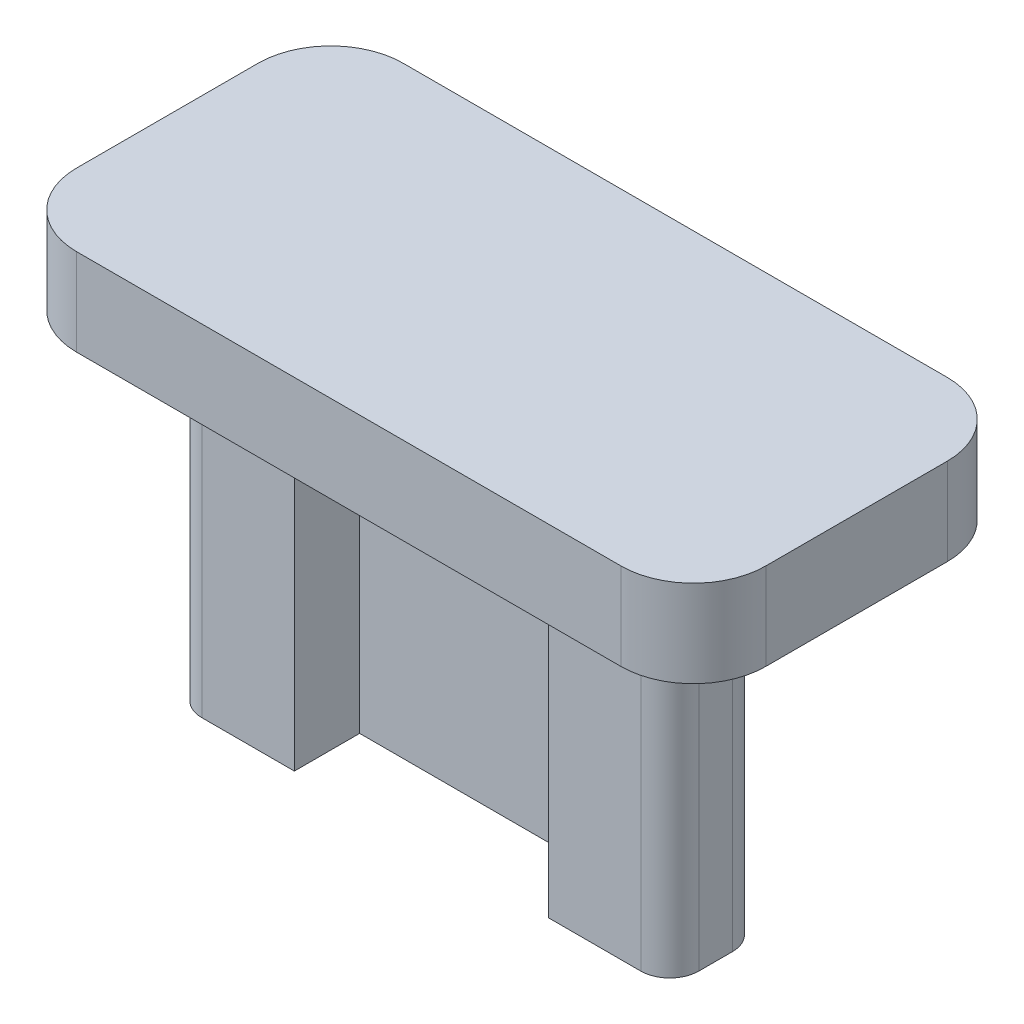
SolidWorks part; units mm, degrees
material "Rubber"
ref_plane "Front Plane" through (0, 0, 0) normal (0, 0, 1) x (1, 0, 0)
ref_plane "Top Plane" through (0, 0, 0) normal (0, 1, 0) x (1, 0, 0)
ref_plane "Right Plane" through (0, 0, 0) normal (1, 0, 0) x (0, 0, -1)
ref_plane "Plane1" through (0, 3.3, 0) normal (0, 1, 0) x (1, 0, 0)
sketch "Sketch1" plane through (0, 3.3, 0) normal (0, 1, 0) x (1, 0, 0)
  line L0 (4.75, -1.9) -> (4.75, 2.6)
  line L1 (4.75, 2.6) -> (-4.75, 2.6)
  line L2 (-4.75, 2.6) -> (-4.75, -1.9)
  line L3 (-4.75, -1.9) -> (4.75, -1.9)
  point P4 (0, 0)
  point P5 (0, -1.9)
extrude "Boss-Extrude1" add sketch "Sketch1" against normal blind 1.2
sketch "Sketch2" plane through (0, 2.1, 0) normal (0, -1, 0) x (1, 0, 0)
  line L0 (3.425, -0.13) -> (2.65, -0.9)
  line L1 (2.65, -0.9) -> (-2.65, -0.9)
  line L2 (-2.65, -0.9) -> (-3.425, -0.13)
  line L3 (-3.425, -0.13) -> (-3.425, 0.9)
  line L4 (-3.425, 0.9) -> (3.425, 0.9)
  line L5 (3.425, 0.9) -> (3.425, -0.13)
extrude "Boss-Extrude2" add sketch "Sketch2" along normal blind 4.5
sketch "Sketch4" plane through (0, -2.4, 0) normal (0, -1, 0) x (1, 0, 0)
  line L0 (1.75, 0.9) -> (-1.75, 0.9)
  line L1 (-1.75, 0.9) -> (-1.75, 0)
  line L2 (-1.75, 0) -> (1.75, 0)
  line L3 (1.75, 0) -> (1.75, 0.9)
  line L4 (3.425, 0.9) -> (-3.425, 0.9) construction
  point P4 (0, 0)
  point P5 (0, 0)
  point P6 (0, 0.9)
  point P8 (0, 0.9)
extrude "Cut-Extrude2" cut sketch "Sketch4" against normal up to surface (4.5 mm away) up to face at (0, 2.1, -0.35)
fillet "Fillet2" radius 0.4 6 edges at (-3.425, -0.15, -0.13) (3.425, -0.15, -0.13) (-3.425, -0.15, 0.9) (-2.65, -0.15, -0.9) (3.425, -0.15, 0.9) (2.65, -0.15, -0.9)
fillet "Fillet3" radius 1 4 edges at (4.75, 2.7, -2.6) (-4.75, 2.7, -2.6) (-4.75, 2.7, 1.9) (4.75, 2.7, 1.9)
